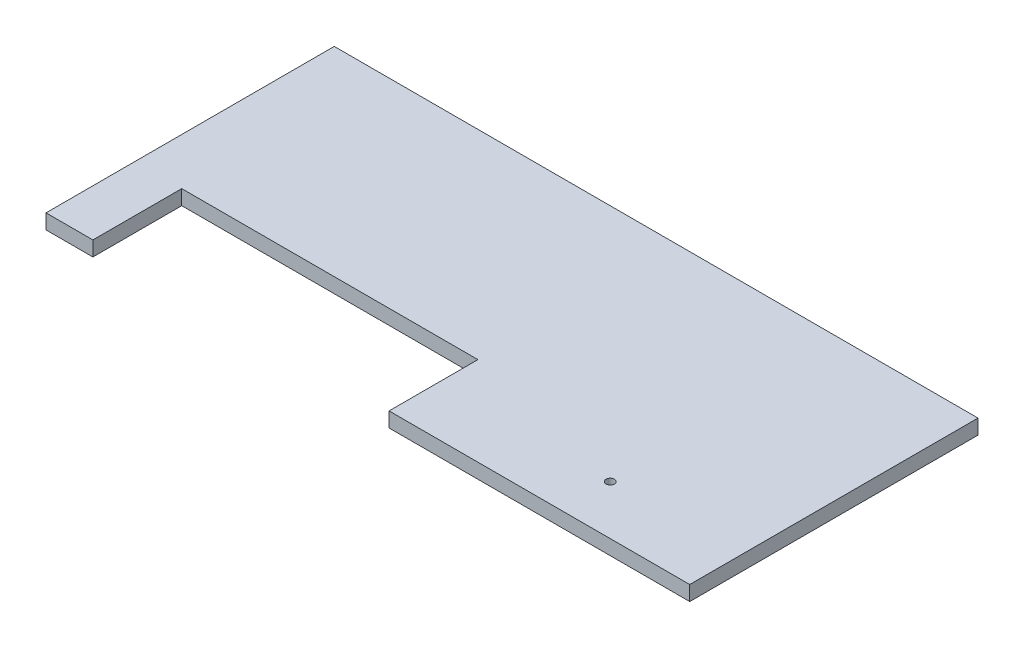
SolidWorks part; units mm, degrees
ref_plane "Front" through (0, 0, 0) normal (0, 0, 1) x (1, 0, 0)
ref_plane "Top" through (0, 0, 0) normal (0, 1, 0) x (1, 0, 0)
ref_plane "Right" through (0, 0, 0) normal (1, 0, 0) x (0, 0, -1)
sketch "Sketch1" plane through (0, 0, 0) normal (0, 1, 0) x (1, 0, 0)
  line L1 (0, 0) -> (130.41, 0)
  line L2 (0, 0) -> (0, -58.4)
  line L3 (0, -58.4) -> (130.41, -58.4)
  line L4 (130.41, 0) -> (130.41, -58.4)
  line L5 (9.5, -40.4) -> (69.5, -40.4)
  line L6 (9.5, -40.4) -> (9.5, -58.4)
  line L7 (9.5, -58.4) -> (69.5, -58.4)
  line L8 (69.5, -40.4) -> (69.5, -58.4)
  dimension "D1" = 130.41
  dimension "D2" = 58.4
  dimension "D3" = 18
  dimension "D4" = 60
  dimension "D5" = 9.5
extrude "Boss-Extrude1" add sketch "Sketch1" along normal blind 3 contours L5 L8 L3 L4 L1 L2 L6
sketch "Sketch2" plane through (0, 3, 0) normal (0, 1, 0) x (1, 0, 0)
  line L0 (69.5, -58.4) -> (130.41, -58.4) construction
  line L1 (130.41, 0) -> (130.41, -58.4) construction
  circle A0 centre (104.3, -48.4) radius 0.85
  dimension "D1" = 1.7
  dimension "D2" = 10
  dimension "D3" = 26.11
extrude "Cut-Extrude1" cut sketch "Sketch2" against normal through all
